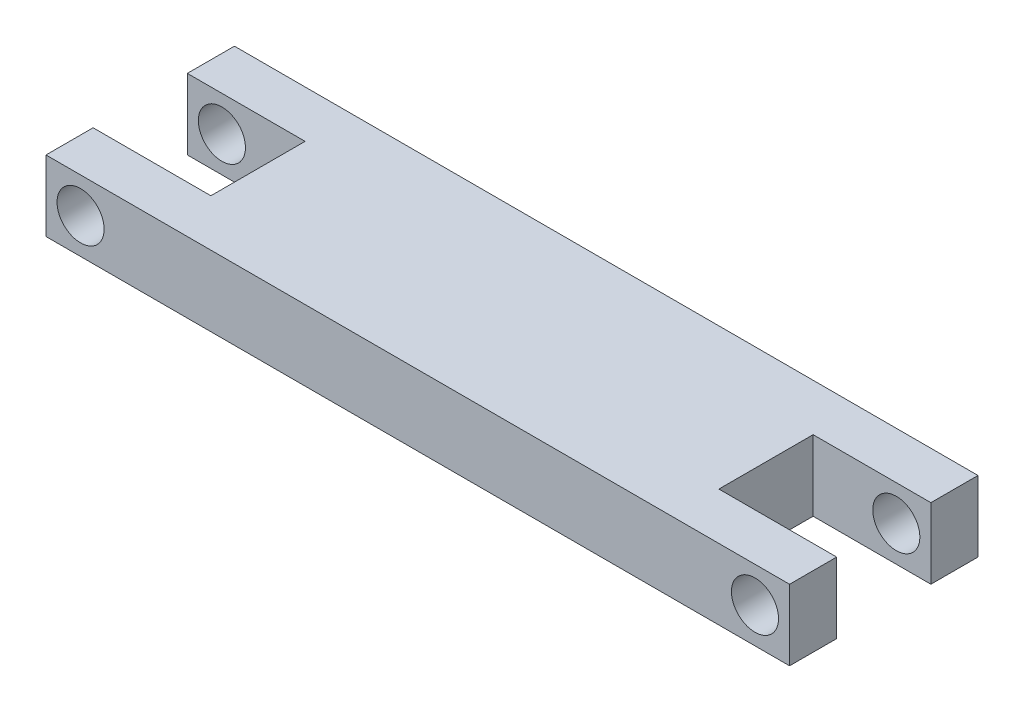
SolidWorks part; units mm, degrees
ref_plane "前视基准面" through (0, 0, 0) normal (0, 0, 1) x (1, 0, 0)
ref_plane "上视基准面" through (0, 0, 0) normal (0, 1, 0) x (1, 0, 0)
ref_plane "右视基准面" through (0, 0, 0) normal (1, 0, 0) x (0, 0, -1)
sketch "草图1" plane through (0, 0, 0) normal (0, 0, 1) x (1, 0, 0)
  line L1 (-73.6404, 15.5702) -> (126.3596, 15.5702)
  line L2 (-73.6404, 15.5702) -> (-73.6404, 0.5702)
  line L3 (-73.6404, 0.5702) -> (126.3596, 0.5702)
  line L4 (126.3596, 15.5702) -> (126.3596, 0.5702)
  line L5 (26.3596, 0.5702) -> (26.3596, 15.5702) construction
  line L6 (-73.6404, 8.0702) -> (126.3596, 8.0702) construction
  circle A0 centre (-66.3006, 8.0702) radius 5
  circle A1 centre (118.6994, 8.0702) radius 5
  point P0 (26.3596, 8.0702)
  dimension "D3" = 0
  dimension "D1" = 200
  dimension "D2" = 15
  dimension "D4" = 2
extrude "凸台-拉伸2" add sketch "草图1" along normal blind 40
sketch "草图2" plane through (0, 15.5702, 0) normal (0, 1, 0) x (1, 0, 0)
  line L0 (-73.6404, -40) -> (-73.6404, 0) construction
  line L1 (-98.6404, -10) -> (-48.6404, -10)
  line L2 (-98.6404, -10) -> (-98.6404, -30)
  line L3 (-98.6404, -30) -> (-48.6404, -30)
  line L4 (-48.6404, -10) -> (-48.6404, -30)
  line L5 (-73.6404, -30) -> (-73.6404, -10) construction
  line L6 (-98.6404, -20) -> (-48.6404, -20) construction
  line L7 (126.3596, 0) -> (-73.6404, 0) construction
  line L8 (101.3596, -10) -> (101.3596, -30)
  line L9 (101.3596, -10) -> (151.3596, -10)
  line L10 (151.3596, -10) -> (151.3596, -30)
  line L11 (101.3596, -30) -> (151.3596, -30)
  point P0 (-73.6404, -20)
  dimension "D1" = 50
  dimension "D2" = 20
  dimension "D3" = 0
  dimension "D4" = 10
  dimension "D5" = 2
extrude "切除-拉伸2" cut sketch "草图2" against normal blind 40
sketch "草图3" plane through (0, 15.5702, 0) normal (0, 1, 0) x (1, 0, 0)
  line L1 (247.4415, 51.1508) -> (5.2778, 51.1508)
  line L2 (247.4415, 51.1508) -> (247.4415, -51.1508)
  line L3 (247.4415, -51.1508) -> (5.2778, -51.1508)
  line L4 (5.2778, 51.1508) -> (5.2778, -51.1508)
  line L5 (126.3596, -51.1508) -> (126.3596, 51.1508) construction
  line L6 (247.4415, 0) -> (5.2778, 0) construction
  point P0 (126.3596, 0)
extrude "切除-拉伸3" cut sketch "草图3" against normal blind 40
mirror "镜向2" about plane through (5.2778, -24.4298, -51.1508) normal (-1, 0, 0) of bodies 105
